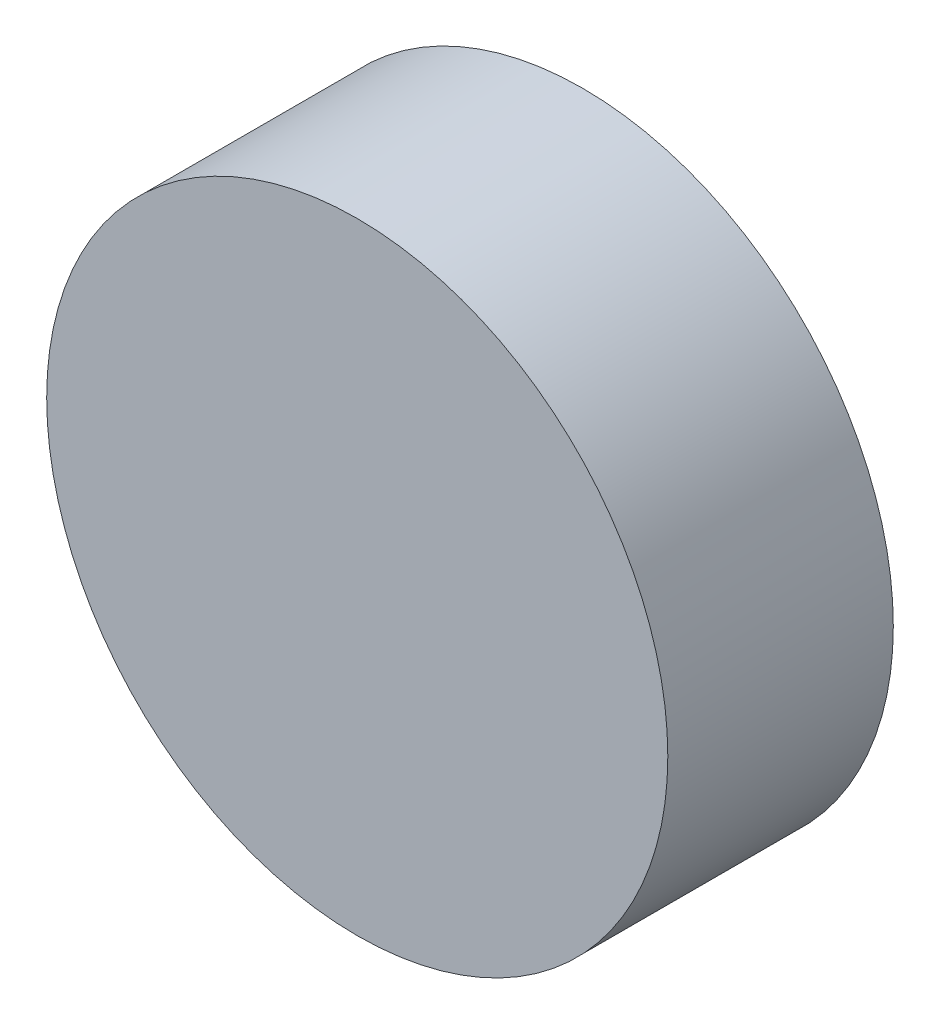
SolidWorks part; units mm, degrees
ref_plane "Front Plane" through (0, 0, 0) normal (0, 0, 1) x (1, 0, 0)
ref_plane "Top Plane" through (0, 0, 0) normal (0, 1, 0) x (1, 0, 0)
ref_plane "Right Plane" through (0, 0, 0) normal (1, 0, 0) x (0, 0, -1)
sketch "Sketch1" plane through (0, 0, 0) normal (0, 0, 1) x (1, 0, 0)
  circle A0 centre (0, 0) radius 23
extrude "Boss-Extrude1" add sketch "Sketch1" along normal blind 16.7
